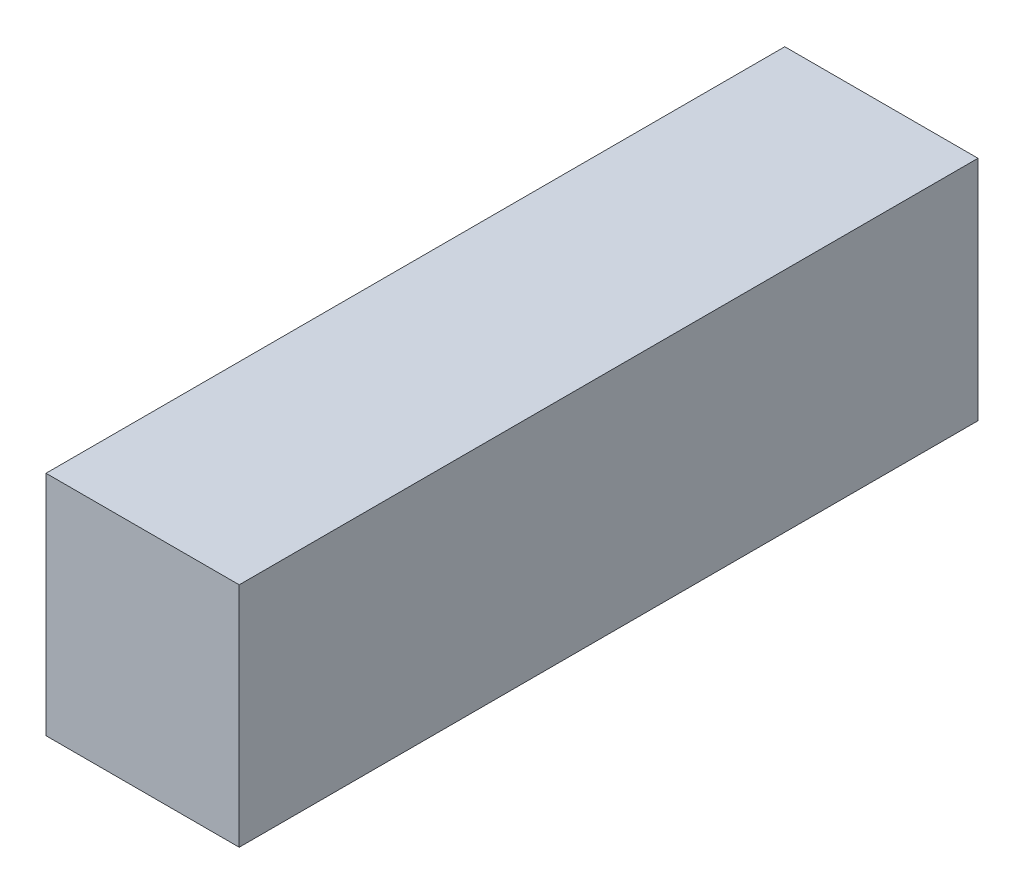
SolidWorks part; units mm, degrees
ref_plane "Front Plane" through (0, 0, 0) normal (0, 0, 1) x (1, 0, 0)
ref_plane "Top Plane" through (0, 0, 0) normal (0, 1, 0) x (1, 0, 0)
ref_plane "Right Plane" through (0, 0, 0) normal (1, 0, 0) x (0, 0, -1)
sketch "Sketch1" plane through (0, 0, 0) normal (0, 0, 1) x (1, 0, 0)
  line L1 (-8.5, -10) -> (8.5, -10)
  line L2 (-8.5, -10) -> (-8.5, 10)
  line L3 (-8.5, 10) -> (8.5, 10)
  line L4 (8.5, -10) -> (8.5, 10)
  line L5 (-8.5, -10) -> (8.5, 10) construction
  line L6 (-8.5, 10) -> (8.5, -10) construction
  point P0 (0, 0)
  dimension "D1" = 17
  dimension "D2" = 20
extrude "Boss-Extrude1" add sketch "Sketch1" along normal mid plane 65
